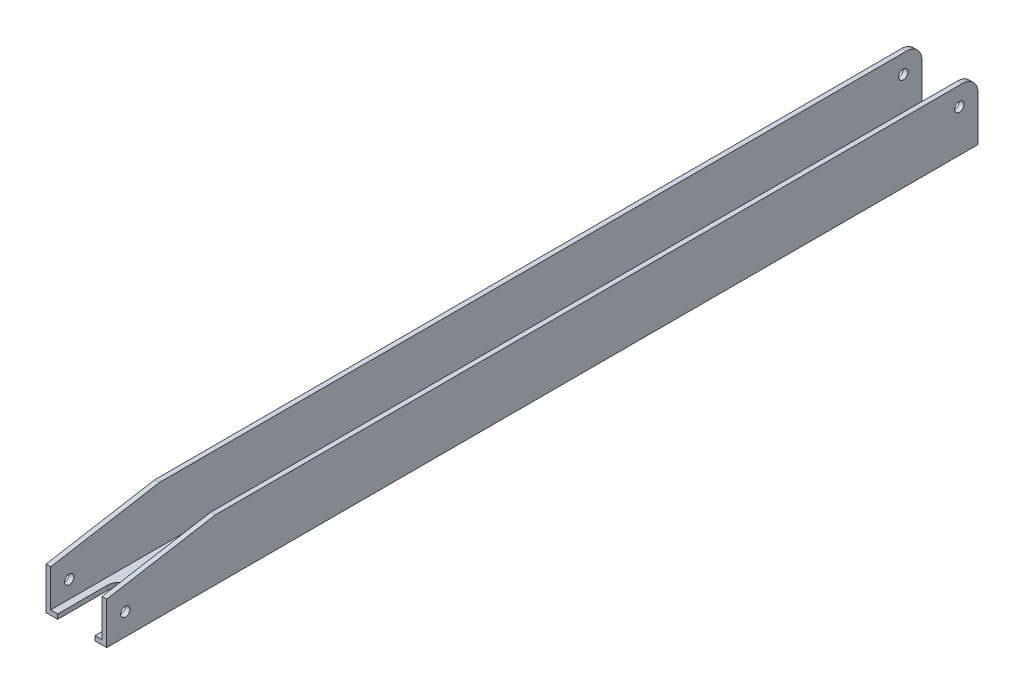
SolidWorks part; units mm, degrees
material "3.0205 (EN-AW 1200)"
ref_plane "Plan de face" through (0, 0, 0) normal (0, 0, 1) x (1, 0, 0)
ref_plane "Plan de dessus" through (0, 0, 0) normal (0, 1, 0) x (1, 0, 0)
ref_plane "Plan de droite" through (0, 0, 0) normal (1, 0, 0) x (0, 0, -1)
sketch "Esquisse1" plane through (0, 0, 0) normal (0, 0, 1) x (1, 0, 0)
  line L0 (-9.75, 19.5) -> (-9.75, 0)
  line L1 (-9.75, 0) -> (9.75, 0)
  line L2 (9.75, 0) -> (9.75, 19.5)
  dimension "D1" = 19.5
  dimension "D2" = 19.5
extrude "Extru.-Mince1" add sketch "Esquisse1" along normal blind 280 thin thin type one direction reverse wall 1.5
sketch "Esquisse2" plane through (0, 0, 0) normal (0, -1, 0) x (1, 0, 0)
  line L0 (-9.75, 280) -> (9.75, 280) construction
  line L1 (-9.75, 0) -> (9.75, 0) construction
  line L4 (-6, 280) -> (6, 280)
  line L5 (-6, 280) -> (-6, 264)
  line L6 (-2, 260) -> (2, 260)
  line L7 (6, 280) -> (6, 264)
  circle A0 centre (0, 223) radius 1.5
  circle A1 centre (0, 205) radius 1.5
  arc A4 (2, 260) -> (6, 264) centre (2, 264) ccw
  arc A5 (-6, 264) -> (-2, 260) centre (-2, 264) ccw
  circle A6 centre (0, 24) radius 1.5
  circle A7 centre (0, 174) radius 1.5
  point P11 (0, 280)
  point P16 (-6, 260)
  point P21 (0, 0)
  dimension "D1" = 18
  dimension "D2" = 3
  dimension "D3" = 57
  dimension "D6" = 4
  dimension "D7" = 24
  dimension "D8" = 150
  dimension "D9" = 3
  dimension "D4" = 12
  dimension "D5" = 20
extrude "Enlèv. mat.-Extru.1" cut sketch "Esquisse2" against normal through all
sketch "Esquisse3" plane through (9.75, 0, 0) normal (1, 0, 0) x (0, 0, -1)
  line L0 (-280, 0) -> (0, 0) construction
  line L1 (0, 0) -> (0, 19.5) construction
  line L2 (-214, 0) -> (-214, -3) construction
  line L4 (-223, 0) -> (-205, 0) construction
  line L5 (-206.5, 0) -> (-203.5, 0) construction
  line L6 (-224.5, 0) -> (-221.5, 0) construction
  line L7 (-280, 13.5) -> (-280, 19.5)
  line L8 (-280, 0) -> (-280, 19.5) construction
  line L9 (-280, 19.5) -> (-245, 19.5)
  line L10 (-280, 19.5) -> (0, 19.5) construction
  line L11 (-245, 19.5) -> (-280, 13.5)
  circle A0 centre (-274, 7) radius 1.5
  circle A1 centre (-6, 13.5) radius 1.5
  dimension "D1" = 3
  dimension "D3" = 60
  dimension "D4" = 3
  dimension "D6" = 6
  dimension "D9" = 6
  dimension "D10" = 6
  dimension "D11" = 3
  dimension "D2" = 10
  dimension "D5" = 6
  dimension "D7" = 35
  dimension "D8" = 13.5
extrude "Enlèv. mat.-Extru.2" cut sketch "Esquisse3" against normal through all
fillet "Congé1" radius 5 2 edges at (-9, 19.5, 0) (9, 19.5, 0)
